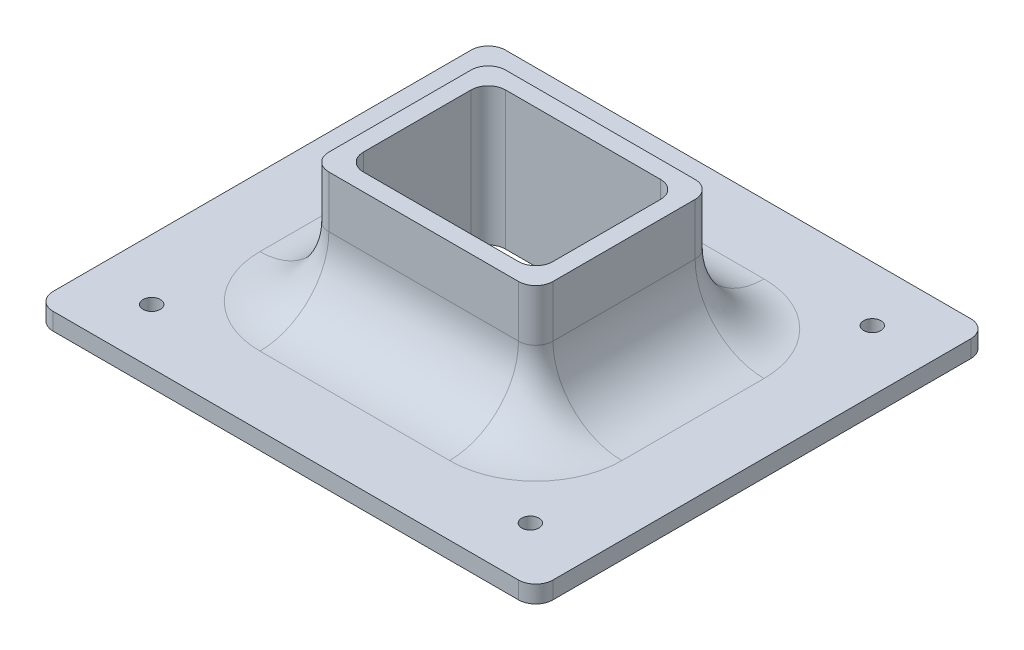
SolidWorks part; units mm, degrees
ref_plane "Front Plane" through (0, 0, 0) normal (0, 0, 1) x (1, 0, 0)
ref_plane "Top Plane" through (0, 0, 0) normal (0, 1, 0) x (1, 0, 0)
ref_plane "Right Plane" through (0, 0, 0) normal (1, 0, 0) x (0, 0, -1)
sketch "Sketch1" plane through (0, 0, 0) normal (0, 1, 0) x (1, 0, 0)
  line L0 (-6.35, 58.7248) -> (76.2, 58.7248)
  line L1 (0, 0) -> (69.85, 0)
  line L2 (0, 0) -> (0, 52.3748)
  line L3 (0, 52.3748) -> (69.85, 52.3748)
  line L4 (69.85, 0) -> (69.85, 52.3748)
  line L5 (76.2, -6.35) -> (76.2, 58.7248)
  line L6 (-6.35, -6.35) -> (76.2, -6.35)
  line L7 (-6.35, -6.35) -> (-6.35, 58.7248)
  dimension "D1" = 52.3748
  dimension "D2" = 69.85
  dimension "D3" = 6.35
extrude "Boss-Extrude1" add sketch "Sketch1" along normal blind 44.45
sketch "Sketch2" plane through (0, 0, 0) normal (0, -1, 0) x (1, 0, 0)
  line L0 (-6.35, -58.7248) -> (-6.35, 6.35) construction
  line L1 (76.2, -58.7248) -> (-6.35, -58.7248) construction
  line L2 (76.2, 6.35) -> (76.2, -58.7248) construction
  line L3 (-6.35, 6.35) -> (76.2, 6.35) construction
  line L4 (-6.35, -58.7248) -> (-6.35, 6.35) construction
  line L5 (76.2, -58.7248) -> (-6.35, -58.7248) construction
  line L6 (76.2, 6.35) -> (76.2, -58.7248) construction
  line L7 (-6.35, 6.35) -> (76.2, 6.35) construction
  line L8 (-57.15, 57.15) -> (127, 57.15)
  line L9 (127, 57.15) -> (127, -109.5248)
  line L10 (127, -109.5248) -> (-57.15, -109.5248)
  line L11 (-57.15, -109.5248) -> (-57.15, 57.15)
  dimension "D1" = 50.8
extrude "Boss-Extrude4" add sketch "Sketch2" along normal blind 6.35
fillet "Fillet2" radius 6.35 12 edges at (127, -3.175, -109.5248) (-57.15, -3.175, -109.5248) (127, -3.175, 57.15) (-57.15, -3.175, 57.15) (0, 22.225, 0) (69.85, 22.225, 0) (69.85, 22.225, -52.3748) (0, 22.225, -52.3748) (-6.35, 22.225, -58.7248) (-6.35, 22.225, 6.35) (76.2, 22.225, -58.7248) (76.2, 22.225, 6.35)
sketch "Sketch3" plane through (0, 0, 0) normal (0, 1, 0) x (1, 0, 0)
  line L0 (-55.2901, 107.6649) -> (125.1401, -55.2901) construction
  line L1 (125.1401, 107.6649) -> (-55.2901, -55.2901) construction
  arc A0 (-50.8, 109.5248) -> (-57.15, 103.1748) centre (-50.8, 103.1748) ccw construction
  arc A1 (120.65, -57.15) -> (127, -50.8) centre (120.65, -50.8) ccw construction
  arc A2 (127, 103.1748) -> (120.65, 109.5248) centre (120.65, 103.1748) ccw construction
  arc A3 (-57.15, -50.8) -> (-50.8, -57.15) centre (-50.8, -50.8) ccw construction
  circle A4 centre (104.6705, 89.1779) radius 3.175
  circle A5 centre (-34.8205, -36.8031) radius 3.175
  circle A6 centre (104.6705, -36.8031) radius 3.175
  circle A7 centre (-34.8205, 89.1779) radius 3.175
  point P20 (34.925, 26.1874)
  dimension "D1" = 6.35
  dimension "D2" = 93.98
extrude "Cut-Extrude1" cut sketch "Sketch3" against normal through all
fillet "Fillet4" radius 25.4 8 edges at (74.3401, 0, -56.8649) (76.2, 0, -26.1874) (74.3401, 0, 4.4901) (34.925, 0, 6.35) (-4.4901, 0, 4.4901) (-6.35, 0, -26.1874) (-4.4901, 0, -56.8649) (34.925, 0, -58.7248)
sketch "Sketch4" plane through (0, 0, 0) normal (0, 1, 0) x (1, 0, 0)
  line L4 (0, 46.0248) -> (0, 6.35)
  line L5 (6.35, 0) -> (63.5, 0)
  line L6 (69.85, 6.35) -> (69.85, 46.0248)
  line L7 (63.5, 52.3748) -> (6.35, 52.3748)
  line L8 (0, 46.0248) -> (0, 6.35)
  line L9 (6.35, 0) -> (63.5, 0)
  line L10 (69.85, 6.35) -> (69.85, 46.0248)
  line L11 (63.5, 52.3748) -> (6.35, 52.3748)
  arc A4 (0, 6.35) -> (6.35, 0) centre (6.35, 6.35) ccw
  arc A5 (63.5, 0) -> (69.85, 6.35) centre (63.5, 6.35) ccw
  arc A6 (69.85, 46.0248) -> (63.5, 52.3748) centre (63.5, 46.0248) ccw
  arc A7 (6.35, 52.3748) -> (0, 46.0248) centre (6.35, 46.0248) ccw
  arc A8 (0, 6.35) -> (6.35, 0) centre (6.35, 6.35) ccw
  arc A9 (63.5, 0) -> (69.85, 6.35) centre (63.5, 6.35) ccw
  arc A10 (69.85, 46.0248) -> (63.5, 52.3748) centre (63.5, 46.0248) ccw
  arc A11 (6.35, 52.3748) -> (0, 46.0248) centre (6.35, 46.0248) ccw
  dimension "D1" = 0
extrude "Cut-Extrude2" cut sketch "Sketch4" against normal through all
